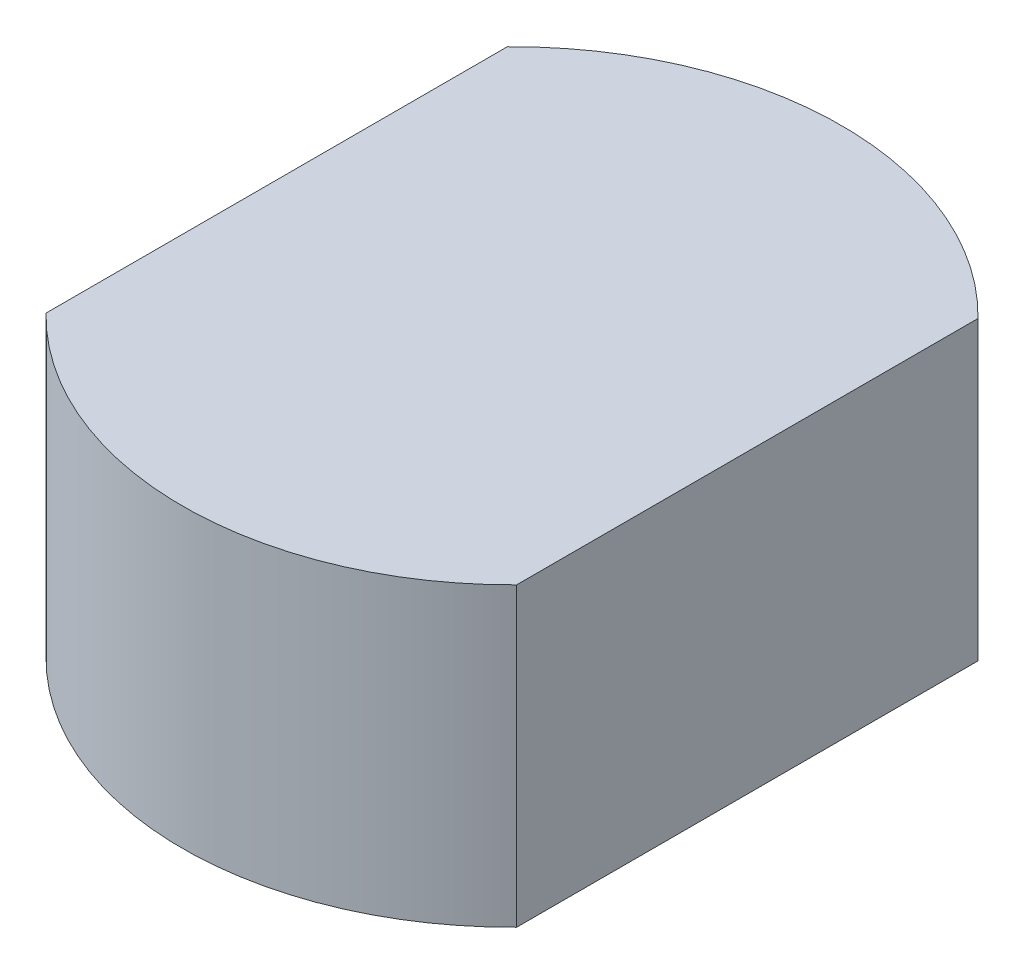
SolidWorks part; units mm, degrees
ref_plane "Ebene vorne" through (0, 0, 0) normal (0, 0, 1) x (1, 0, 0)
ref_plane "Ebene oben" through (0, 0, 0) normal (0, 1, 0) x (1, 0, 0)
ref_plane "Ebene rechts" through (0, 0, 0) normal (1, 0, 0) x (0, 0, -1)
sketch "Skizze1" plane through (0, 0, 0) normal (0, 1, 0) x (1, 0, 0)
  line L2 (7.1414, 7) -> (7.1414, -7)
  line L4 (-7.1414, -7) -> (-7.1414, 7)
  arc A0 (7.1414, 7) -> (-7.1414, 7) centre (0, 0) ccw
  arc A1 (-7.1414, -7) -> (7.1414, -7) centre (0, 0) ccw
extrude "Aufsatz-Linear austragen1" add sketch "Skizze1" along normal blind 9 contours L4 A0 L2 A1
